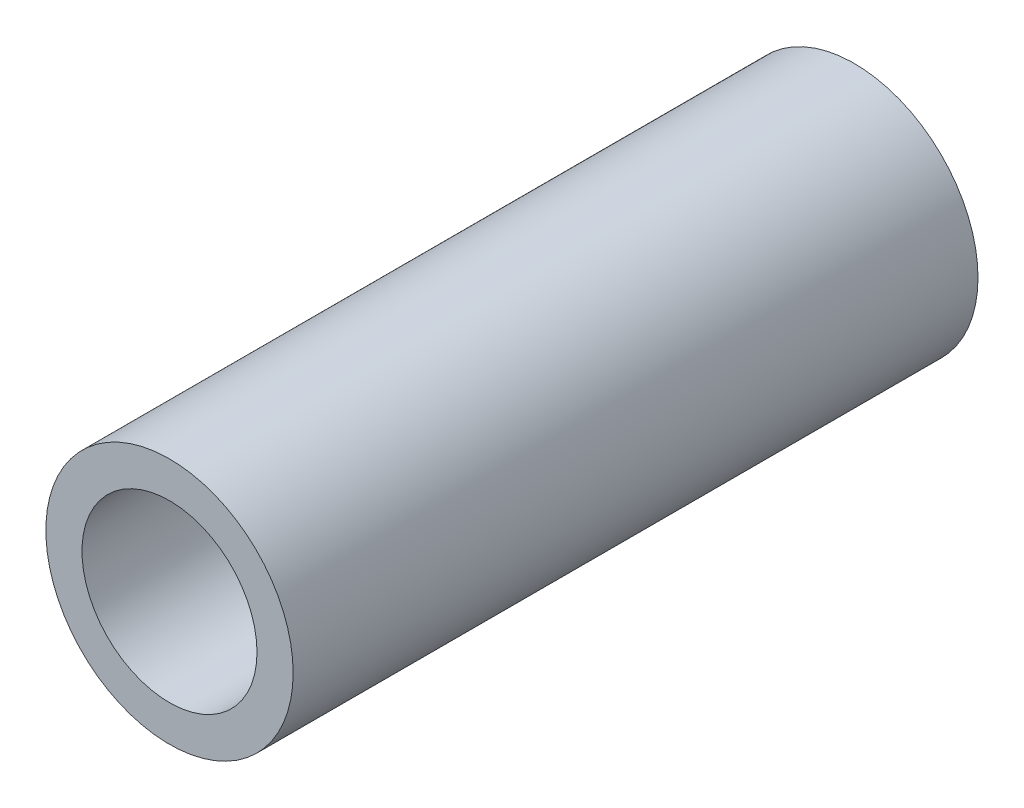
SolidWorks part; units mm, degrees
ref_plane "Front Plane" through (0, 0, 0) normal (0, 0, 1) x (1, 0, 0)
ref_plane "Top Plane" through (0, 0, 0) normal (0, 1, 0) x (1, 0, 0)
ref_plane "Right Plane" through (0, 0, 0) normal (1, 0, 0) x (0, 0, -1)
sketch "Sketch1" plane through (0, 0, 0) normal (0, 0, 1) x (1, 0, 0)
  circle A0 centre (0, 0) radius 2.3
  circle A1 centre (0, 0) radius 3.25
  dimension "D1" = 4.6
  dimension "D2" = 6.5
extrude "Boss-Extrude1" add sketch "Sketch1" along normal blind 18
